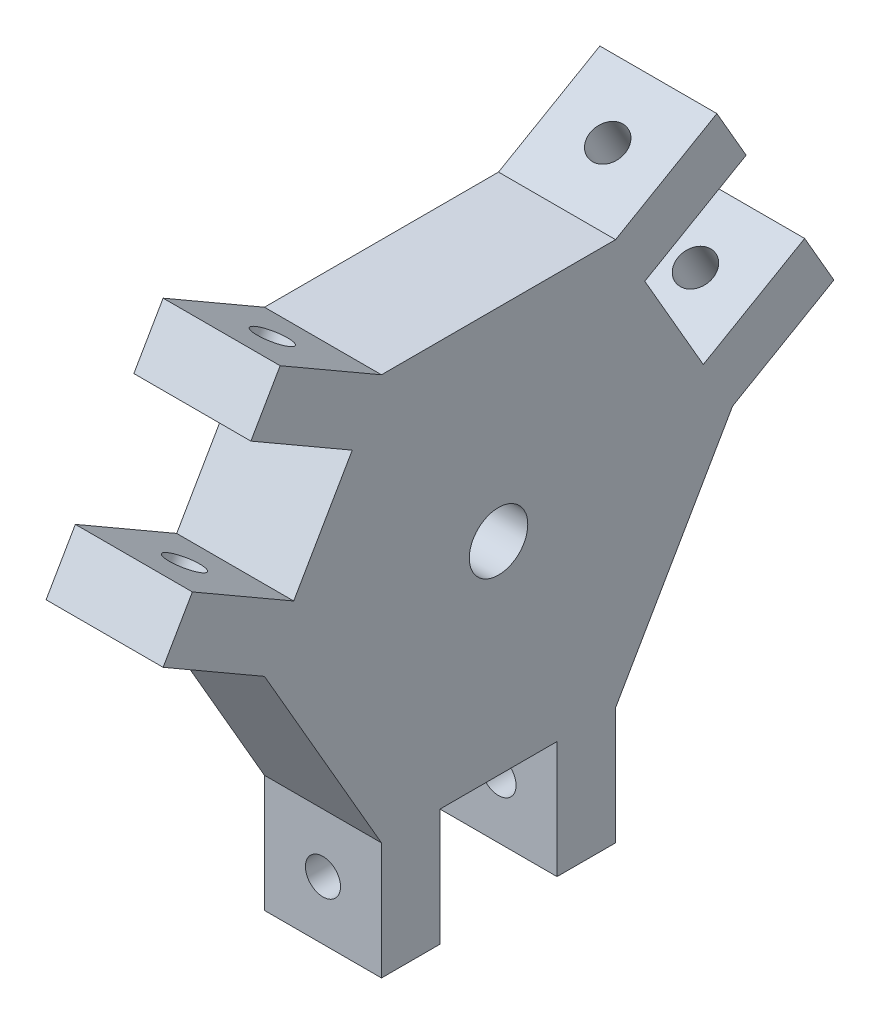
SolidWorks part; units mm, degrees
ref_plane "前视基准面" through (0, 0, 0) normal (0, 0, 1) x (1, 0, 0)
ref_plane "上视基准面" through (0, 0, 0) normal (0, 1, 0) x (1, 0, 0)
ref_plane "右视基准面" through (0, 0, 0) normal (1, 0, 0) x (0, 0, -1)
other "Configuration Table"
sketch "草图1" plane through (0, 0, 0) normal (1, 0, 0) x (0, 0, -1)
  line L6 (20, -34.641) -> (-20, -34.641)
  line L7 (-20, -34.641) -> (-40, 0)
  line L8 (-40, 0) -> (-20, 34.641)
  line L9 (-20, 34.641) -> (20, 34.641)
  line L10 (40, 0) -> (20, 34.641)
  line L11 (40, 0) -> (20, -34.641)
extrude "凸台-拉伸1" add sketch "草图1" along normal blind 20
sketch "草图2" plane through (0, 17.3205, 30) normal (0, 0.5, 0.866) x (1, 0, 0)
  line L0 (20, 20) -> (20, -20) construction
  line L1 (0, 20) -> (20, 20)
  line L2 (0, 20) -> (0, 10)
  line L3 (0, 10) -> (20, 10)
  line L4 (20, 20) -> (20, 10)
  dimension "D1" = 10
extrude "凸台-拉伸2" add sketch "草图2" along normal blind 20
sketch "草图3" plane through (0, 17.3205, 30) normal (0, 0.5, 0.866) x (1, 0, 0)
  line L0 (20, 10) -> (20, -20) construction
  line L1 (0, -20) -> (20, -20)
  line L2 (0, -20) -> (0, -10)
  line L3 (0, -10) -> (20, -10)
  line L4 (20, -20) -> (20, -10)
  dimension "D1" = 10
extrude "凸台-拉伸3" add sketch "草图3" along normal blind 20
sketch "草图4" plane through (0, 17.3205, -10) normal (0, 0.866, -0.5) x (1, 0, 0)
  circle A0 centre (10, -44.641) radius 3
extrude "切除-拉伸1" cut sketch "草图4" against normal through all both and the other way through all
sketch "草图5" plane through (20, 0, 0) normal (1, 0, 0) x (0, 0, -1)
  circle A0 centre (0, 0) radius 5
extrude "切除-拉伸2" cut sketch "草图5" against normal through all and the other way through all
pattern_circular "阵列(圆周)1" count 3 over 360 about axis through (0, 0, 0) along (1, 0, 0) of "凸台-拉伸2", "凸台-拉伸3", "切除-拉伸1"
